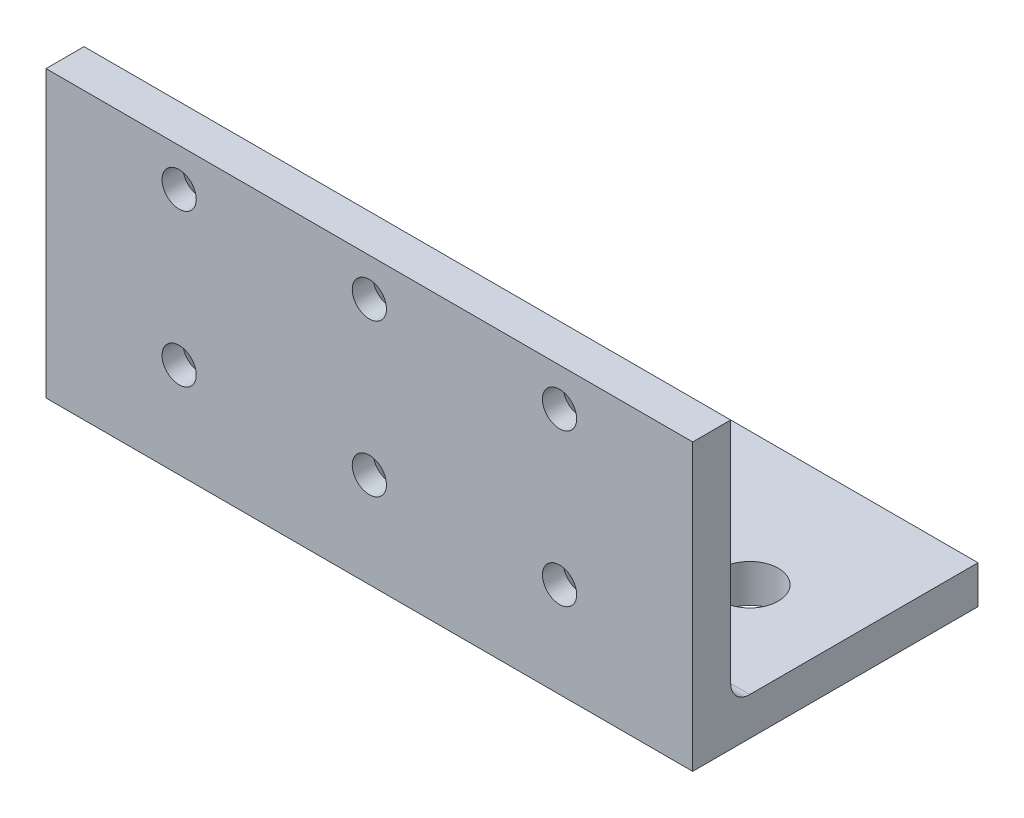
SolidWorks part; units mm, degrees
ref_plane "Front Plane" through (0, 0, 0) normal (0, 0, 1) x (1, 0, 0)
ref_plane "Top Plane" through (0, 0, 0) normal (0, 1, 0) x (1, 0, 0)
ref_plane "Right Plane" through (0, 0, 0) normal (1, 0, 0) x (0, 0, -1)
sketch "Sketch1" plane through (0, 0, 0) normal (1, 0, 0) x (0, 0, -1)
  line L0 (0, 15) -> (0, 0)
  line L1 (0, 0) -> (15, 0)
  line L2 (15, 0) -> (15, 2)
  line L3 (15, 2) -> (2, 2)
  line L4 (2, 2) -> (2, 15)
  line L5 (2, 15) -> (0, 15)
  dimension "D1" = 2
  dimension "D2" = 2
  dimension "D3" = 15
  dimension "D4" = 15
extrude "Boss-Extrude1" add sketch "Sketch1" along normal blind 34
fillet "Fillet1" radius 1 1 edges at (17, 2, -2)
sketch "Sketch2" plane through (0, 0, 0) normal (0, -1, 0) x (1, 0, 0)
  line L0 (34, 0) -> (34, -15) construction
  line L1 (34, 0) -> (0, 0) construction
  line L2 (0, 0) -> (0, -15) construction
  circle A0 centre (29, -8) radius 1.5
  circle A1 centre (5, -8) radius 1.5
  dimension "D2" = 3
  dimension "D5" = 3
  dimension "D1" = 5
  dimension "D3" = 8
  dimension "D4" = 8
  dimension "D6" = 5
extrude "Cut-Extrude3" cut sketch "Sketch2" against normal blind 10
sketch "Sketch3" plane through (0, 0, -2) normal (0, 0, -1) x (-1, 0, 0)
  line L0 (-17, 15) -> (-17, 3) construction
  line L1 (-34, 15) -> (0, 15) construction
  line L2 (-34, 3) -> (0, 3) construction
  circle A0 centre (-17, 13) radius 1.5
  circle A1 centre (-17, 5) radius 1.5
  point P6 (-17, 13)
  point P8 (-17, 5)
  dimension "D2" = 3
  dimension "D3" = 3
  dimension "D1" = 2
  dimension "D4" = 2
hole_wizard "CSK for M1.6 Countersunk Flat Head Screw1" positions "Sketch3" profile "Sketch4" countersink size "M1.6" standard "ISO"
sketch "Sketch4" plane through (17, 5, -2) normal (1, 0, 0) x (0, 1, 0)
  line L0 (0, 0) -> (0, 30.5408)
  line L1 (0, 30.5408) -> (0.9, 30)
  line L2 (0.9, 30) -> (0.9, 0.9)
  line L3 (0.9, 0.9) -> (1.8, 0)
  line L5 (1.8, 0) -> (0, 0)
  line L6 (-0.9, 0.9) -> (-1.8, 0) construction
  line L10 (0, 30.5408) -> (-0.9, 30) construction
  line L11 (0, -6.35) -> (0, 107.95) construction
  dimension "Hole Dia." = 1.8
  dimension "Hole Depth" = 30
  dimension "Near C'Sink Dia." = 3.6
  dimension "Near C'Sink Angle" = 90
  dimension "Drill Angle" = 118
pattern_linear "LPattern1" count 2 spacing 10 along (-1, 0, 0) of "CSK for M1.6 Countersunk Flat Head Screw1"
pattern_linear "LPattern2" count 2 spacing 10 along (1, 0, 0) of "CSK for M1.6 Countersunk Flat Head Screw1"
